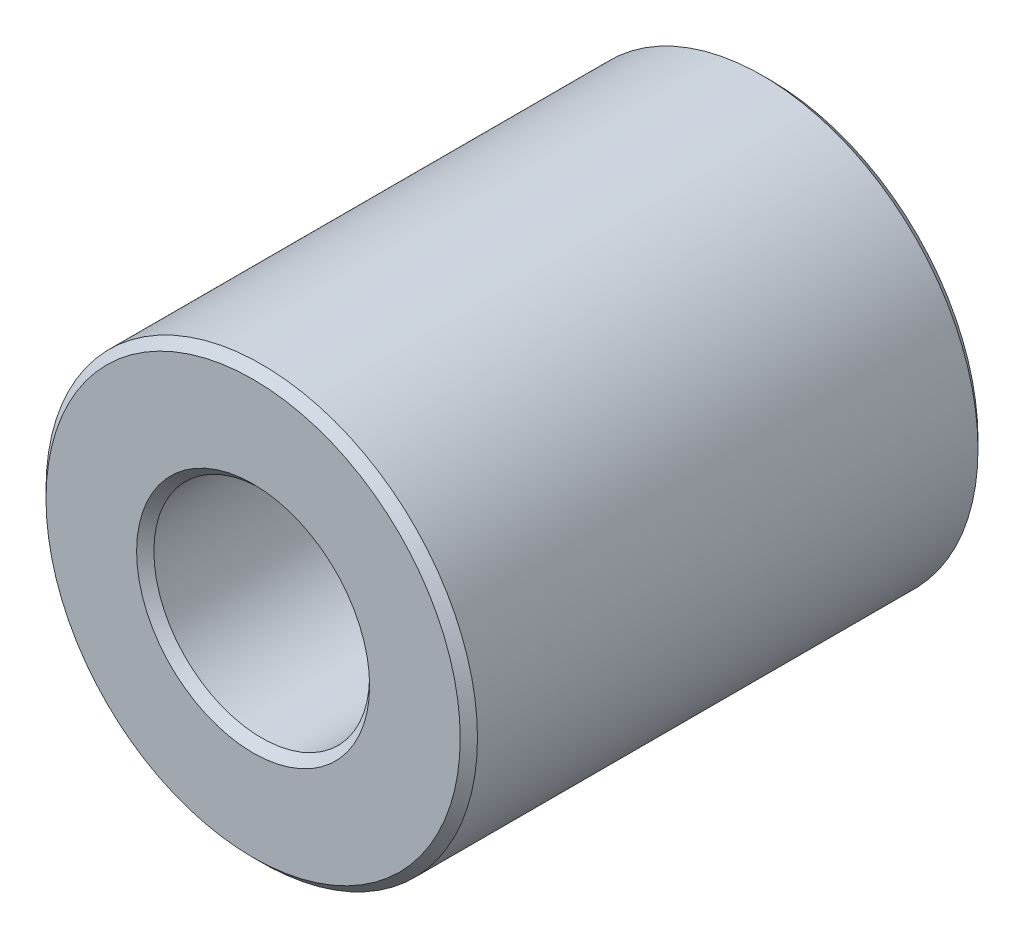
SolidWorks part; units mm, degrees
ref_plane "Alzado" through (0, 0, 0) normal (0, 0, 1) x (1, 0, 0)
ref_plane "Planta" through (0, 0, 0) normal (0, 1, 0) x (1, 0, 0)
ref_plane "Vista lateral" through (0, 0, 0) normal (1, 0, 0) x (0, 0, -1)
sketch "Croquis1" plane through (0, 0, 0) normal (0, 0, 1) x (1, 0, 0)
  circle A0 centre (0, 0) radius 12.5
  circle A1 centre (0, 0) radius 25
  dimension "D1" = 50
  dimension "D2" = 25
extrude "Saliente-Extruir1" add sketch "Croquis1" along normal blind 60
chamfer "Chaflán1" distance 1 angle 45 4 edges at (12.5, 0, 0) (25, 0, 0) (12.5, 0, 60) (25, 0, 60)
